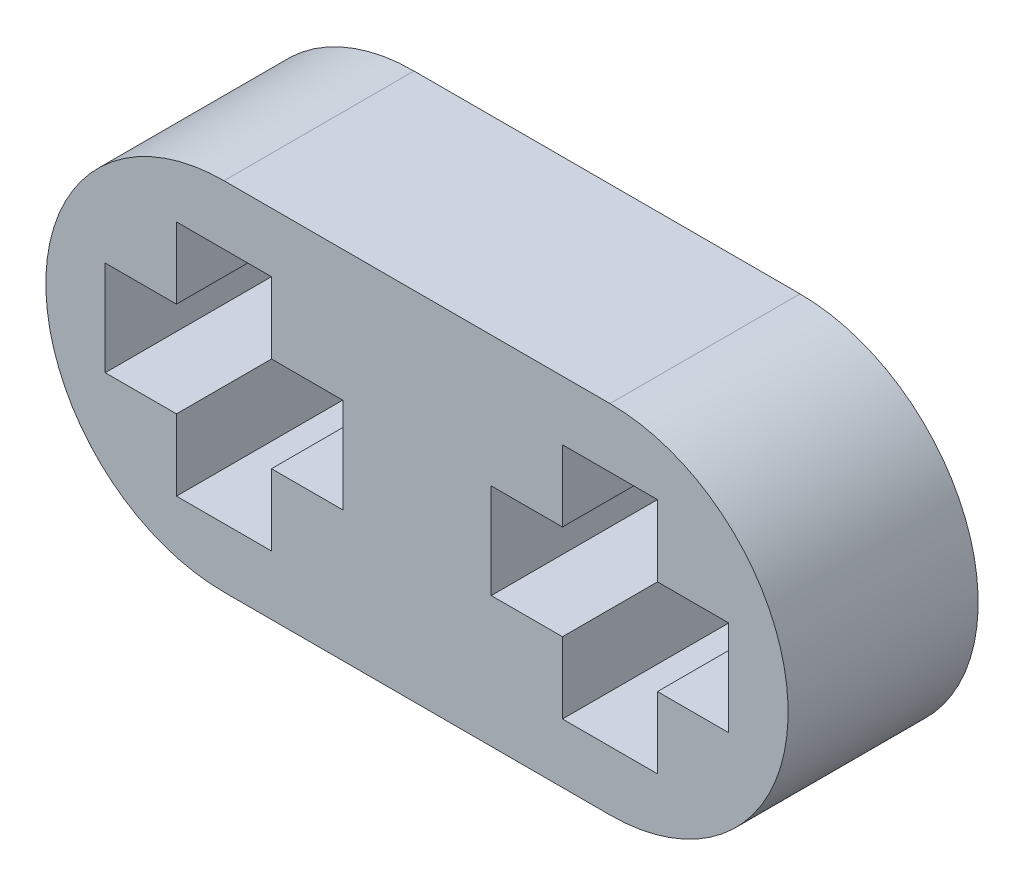
SolidWorks part; units mm, degrees
material "PVC 0.007 Plasticized"
ref_plane "Front Plane" through (0, 0, 0) normal (0, 0, 1) x (1, 0, 0)
ref_plane "Top Plane" through (0, 0, 0) normal (0, 1, 0) x (1, 0, 0)
ref_plane "Right Plane" through (0, 0, 0) normal (1, 0, 0) x (0, 0, -1)
sketch "Sketch1" plane through (0, 0, 0) normal (0, 0, 1) x (1, 0, 0)
  line L0 (0, 0) -> (8.125, 0)
  line L1 (8.125, 0) -> (8.125, 2.5)
  line L2 (8.125, 2.5) -> (9.125, 2.5)
  line L3 (9.125, 2.5) -> (9.125, 1)
  line L4 (9.125, 1) -> (10.625, 1)
  line L5 (10.625, 1) -> (10.625, -1)
  line L6 (10.625, -1) -> (9.125, -1)
  line L7 (9.125, -1) -> (9.125, -2.5)
  line L8 (9.125, -2.5) -> (7.125, -2.5)
  line L9 (7.125, -2.5) -> (7.125, -1)
  line L10 (7.125, -1) -> (5.625, -1)
  line L11 (5.625, -1) -> (5.625, 1)
  line L12 (5.625, 1) -> (7.125, 1)
  line L13 (7.125, 1) -> (7.125, 2.5)
  line L14 (7.125, 2.5) -> (8.125, 2.5)
  line L16 (1, 1) -> (1, 2.5)
  line L17 (2.5, 1) -> (1, 1)
  line L18 (2.5, -1) -> (2.5, 1)
  line L19 (1, -1) -> (2.5, -1)
  line L20 (1, -2.5) -> (1, -1)
  line L21 (-1, -2.5) -> (1, -2.5)
  line L22 (-1, -1) -> (-1, -2.5)
  line L23 (-2.5, -1) -> (-1, -1)
  line L24 (-2.5, 1) -> (-2.5, -1)
  line L25 (-1, 1) -> (-2.5, 1)
  line L26 (-1, 2.5) -> (-1, 1)
  line L27 (0, 2.5) -> (-1, 2.5)
  line L28 (1, 2.5) -> (0, 2.5)
  line L29 (0, 3.75) -> (8.125, 3.75)
  line L30 (8.125, -3.75) -> (0, -3.75)
  arc A0 (0, 3.75) -> (0, -3.75) centre (0, 0) ccw
  arc A1 (8.125, -3.75) -> (8.125, 3.75) centre (8.125, 0) ccw
extrude "Boss-Extrude1" add sketch "Sketch1" along normal blind 4
